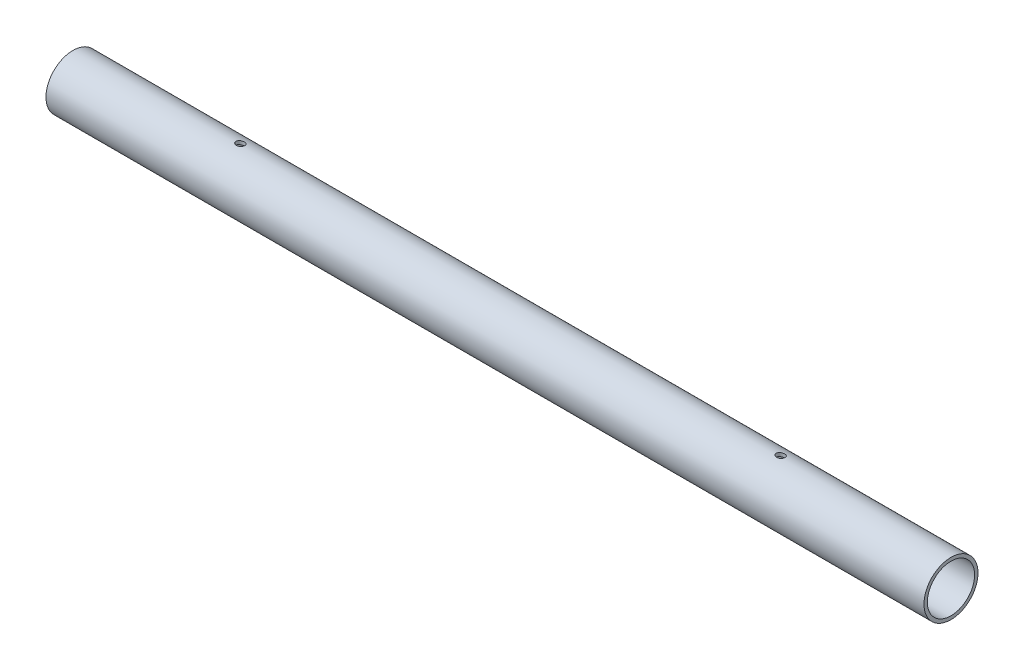
SolidWorks part; units mm, degrees
ref_plane "Front Plane" through (0, 0, 0) normal (0, 0, 1) x (1, 0, 0)
ref_plane "Top Plane" through (0, 0, 0) normal (0, 1, 0) x (1, 0, 0)
ref_plane "Right Plane" through (0, 0, 0) normal (1, 0, 0) x (0, 0, -1)
sketch "Sketch2" plane through (0, 0, 0) normal (1, 0, 0) x (0, 0, -1)
  circle A0 centre (0, 0) radius 20
  circle A1 centre (0, 0) radius 17.5
  dimension "D1" = 40
  dimension "D2" = 35
extrude "Boss-Extrude1" add sketch "Sketch2" along normal blind 650
sketch "Sketch3" plane through (0, 0, 0) normal (0, 1, 0) x (1, 0, 0)
  line L0 (650, 20) -> (0, 20) construction
  line L2 (0, 20) -> (0, -20) construction
  line L3 (650, -20) -> (650, 20) construction
  circle A0 centre (121.468, 2.5) radius 3
  circle A1 centre (521.468, 2.5) radius 3
  dimension "D3" = 6
  dimension "D4" = 6
  dimension "D1" = 400
  dimension "D2" = 17.5
  dimension "D5" = 121.468
  dimension "D6" = 128.532
extrude "Cut-Extrude1" cut sketch "Sketch3" against normal mid plane 60
